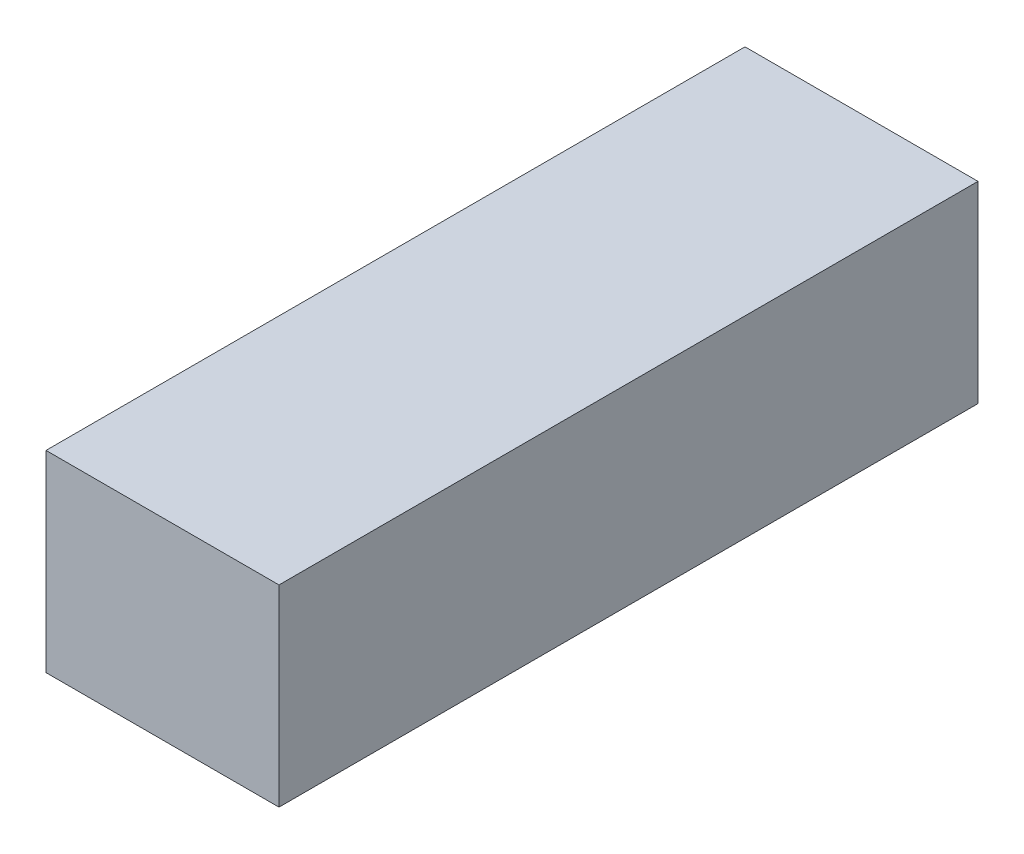
SolidWorks part; units mm, degrees
ref_plane "Front Plane" through (0, 0, 0) normal (0, 0, 1) x (1, 0, 0)
ref_plane "Top Plane" through (0, 0, 0) normal (0, 1, 0) x (1, 0, 0)
ref_plane "Right Plane" through (0, 0, 0) normal (1, 0, 0) x (0, 0, -1)
sketch "Sketch1" plane through (0, 0, 0) normal (0, 1, 0) x (1, 0, 0)
  line L0 (0, 0) -> (0, -138)
  line L1 (0, -138) -> (-46, -138)
  line L2 (0, 0) -> (-46, 0)
  line L3 (-46, 0) -> (-46, -138)
extrude "Boss-Extrude1" add sketch "Sketch1" along normal blind 38
